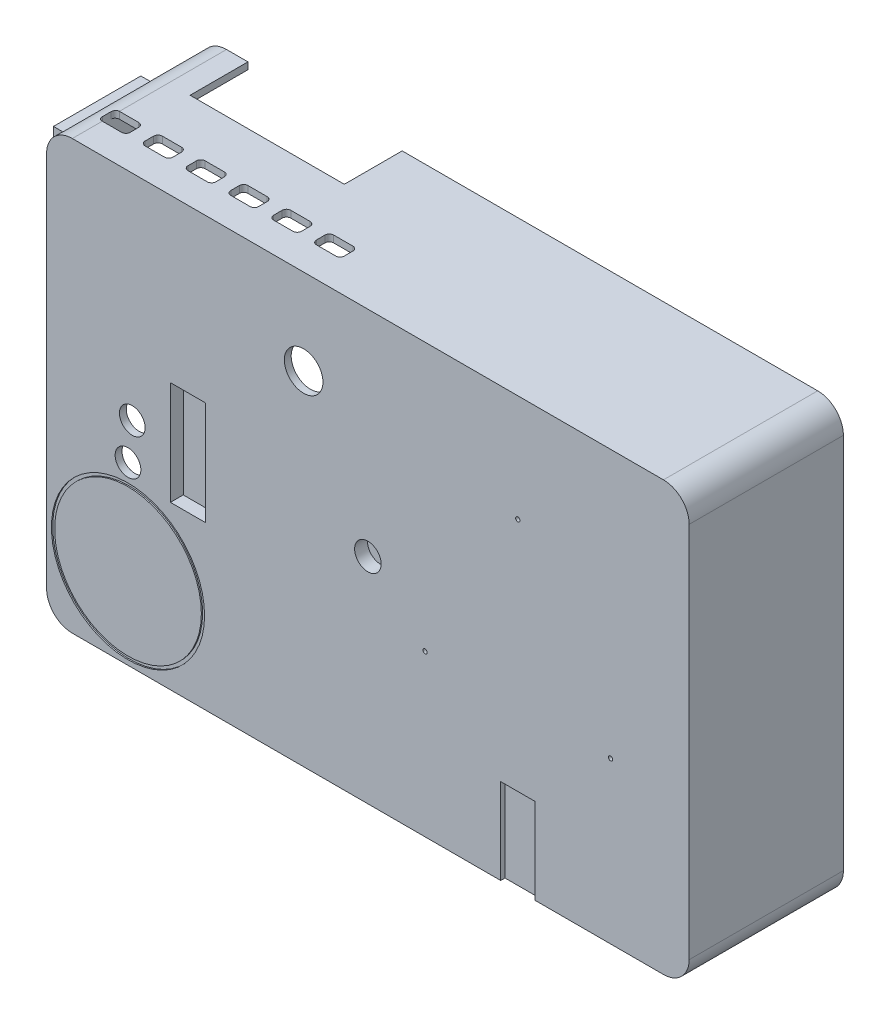
SolidWorks part; units mm, degrees
ref_plane "Front Plane" through (0, 0, 0) normal (0, 0, 1) x (1, 0, 0)
ref_plane "Top Plane" through (0, 0, 0) normal (0, 1, 0) x (1, 0, 0)
ref_plane "Right Plane" through (0, 0, 0) normal (1, 0, 0) x (0, 0, -1)
sketch "Sketch1" plane through (0, 0, 0) normal (0, 0, 1) x (1, 0, 0)
  line L0 (-138, -100) -> (138, -100)
  line L1 (150, -88) -> (150, 88)
  line L2 (138, 100) -> (-138, 100)
  line L3 (-150, 88) -> (-150, -88)
  arc A0 (138, -100) -> (150, -88) centre (138, -88) ccw
  arc A1 (150, 88) -> (138, 100) centre (138, 88) ccw
  arc A2 (-138, 100) -> (-150, 88) centre (-138, 88) ccw
  arc A3 (-150, -88) -> (-138, -100) centre (-138, -88) ccw
extrude "Plinth_block" add sketch "Sketch1" along normal blind 72
ref_plane "Plane_Z+34.15" through (0, 0, 34.15) normal (0, 0, 1) x (1, 0, 0)
sketch "Sketch2" plane through (0, 0, 34.15) normal (0, 0, 1) x (1, 0, 0)
  line L0 (-151, -96.8) -> (-9, -96.8)
  line L1 (-9, -96.8) -> (-9, 96.8)
  line L2 (-9, 96.8) -> (-151, 96.8)
  line L3 (-151, 96.8) -> (-151, -96.8)
  line L4 (3.2, -96.8) -> (137.8, -96.8)
  line L5 (146.8, -87.8) -> (146.8, 87.8)
  line L6 (137.8, 96.8) -> (3.2, 96.8)
  line L7 (-5.8, 87.8) -> (-5.8, -87.8)
  arc A0 (137.8, -96.8) -> (146.8, -87.8) centre (137.8, -87.8) ccw
  arc A1 (146.8, 87.8) -> (137.8, 96.8) centre (137.8, 87.8) ccw
  arc A2 (3.2, 96.8) -> (-5.8, 87.8) centre (3.2, 87.8) ccw
  arc A3 (-5.8, -87.8) -> (3.2, -96.8) centre (3.2, -87.8) ccw
extrude "Hollow_bay_and_front_void" cut sketch "Sketch2" against normal mid plane 69.3
sketch "Sketch3" plane through (0, 0, 0) normal (0, 0, 1) x (1, 0, 0)
  line L0 (-5.8, 38.8) -> (146.8, 38.8)
  line L1 (146.8, 38.8) -> (146.8, 41.2)
  line L2 (146.8, 41.2) -> (-5.8, 41.2)
  line L3 (-5.8, 41.2) -> (-5.8, 38.8)
  line L4 (-5.8, -41.2) -> (146.8, -41.2)
  line L5 (146.8, -41.2) -> (146.8, -38.8)
  line L6 (146.8, -38.8) -> (-5.8, -38.8)
  line L7 (-5.8, -38.8) -> (-5.8, -41.2)
extrude "Dish_support_ribs" add sketch "Sketch3" along normal blind 68.8
ref_plane "Plane_Z+64.00" through (0, 0, 64) normal (0, 0, 1) x (1, 0, 0)
sketch "Sketch4" plane through (0, 0, 64) normal (0, 0, 1) x (1, 0, 0)
  circle A0 centre (70, 0) radius 64
extrude "Dish_floor_thickening" add sketch "Sketch4" along normal blind 4.8
ref_plane "Plane_Z+20.00" through (0, 0, 20) normal (0, 0, 1) x (1, 0, 0)
sketch "Sketch5" plane through (0, 0, 20) normal (0, 0, 1) x (1, 0, 0)
  circle A0 centre (0, 0) radius 12
extrude "Rod_socket_boss" add sketch "Sketch5" along normal blind 48.8
ref_plane "Plane_Z+60.00" through (0, 0, 60) normal (0, 0, 1) x (1, 0, 0)
sketch "Sketch6" plane through (0, 0, 60) normal (0, 0, 1) x (1, 0, 0)
  line L0 (-95, -27) -> (-73, -27)
  line L1 (-73, -27) -> (-73, 27)
  line L2 (-73, 27) -> (-95, 27)
  line L3 (-95, 27) -> (-95, -27)
extrude "Mortise_block" add sketch "Sketch6" along normal blind 8.8
ref_plane "Plane_Z+28.00" through (0, 0, 28) normal (0, 0, 1) x (1, 0, 0)
sketch "Sketch7" plane through (0, 0, 28) normal (0, 0, 1) x (1, 0, 0)
  line L0 (-150, 84) -> (-140, 84)
  line L1 (-140, 84) -> (-140, 97.3)
  line L2 (-140, 97.3) -> (-150, 97.3)
  line L3 (-150, 97.3) -> (-150, 84)
  line L4 (-150, -84) -> (-140, -84)
  line L5 (-140, -84) -> (-140, -97.3)
  line L6 (-140, -97.3) -> (-150, -97.3)
  line L7 (-150, -97.3) -> (-150, -84)
extrude "End_panel_screw_bosses" add sketch "Sketch7" along normal blind 40.8
ref_plane "Plane_Z+69.50" through (0, 0, 69.5) normal (0, 0, 1) x (1, 0, 0)
sketch "Sketch8" plane through (0, 0, 69.5) normal (0, 0, 1) x (1, 0, 0)
  circle A0 centre (0, 0) radius 6.2
  dimension "RodBore" = 12.4
extrude "Rod_socket" cut sketch "Sketch8" against normal mid plane 7
sketch "Sketch9" plane through (0, 0, 69.5) normal (0, 0, 1) x (1, 0, 0)
  line L0 (-92.2, -24.2) -> (-75.8, -24.2)
  line L1 (-75.8, -24.2) -> (-75.8, 24.2)
  line L2 (-75.8, 24.2) -> (-92.2, 24.2)
  line L3 (-92.2, 24.2) -> (-92.2, -24.2)
extrude "Column_mortise" cut sketch "Sketch9" against normal mid plane 7
ref_plane "Plane_Z+70.50" through (0, 0, 70.5) normal (0, 0, 1) x (1, 0, 0)
sketch "Sketch10" plane through (0, 0, 70.5) normal (0, 0, 1) x (1, 0, 0)
  circle A0 centre (70, 50) radius 1
  circle A1 centre (26.6987, -25) radius 1
  circle A2 centre (113.3013, -25) radius 1
extrude "Seat_pin_holes" cut sketch "Sketch10" against normal mid plane 5
ref_plane "Plane_Z+71.50" through (0, 0, 71.5) normal (0, 0, 1) x (1, 0, 0)
sketch "Sketch11" plane through (0, 0, 71.5) normal (0, 0, 1) x (1, 0, 0)
  line L0 (62, -101) -> (78, -101)
  line L1 (78, -101) -> (78, -60)
  line L2 (78, -60) -> (62, -60)
  line L3 (62, -60) -> (62, -101)
extrude "Spill_drain_channel" cut sketch "Sketch11" against normal mid plane 3
ref_plane "Plane_Z+72.20" through (0, 0, 72.2) normal (0, 0, 1) x (1, 0, 0)
sketch "Sketch12" plane through (0, 0, 72.2) normal (0, 0, 1) x (1, 0, 0)
  circle A0 centre (-112, -62) radius 35.75
  circle A1 centre (-112, -62) radius 34.25
extrude "Bottle_position_marker_groove" cut sketch "Sketch12" against normal mid plane 1.6
sketch "Sketch13" plane through (0, 0, 0) normal (0, 0, 1) x (1, 0, 0)
  circle A0 centre (-30, 60) radius 9
  circle A1 centre (-110, 0) radius 6
  circle A2 centre (-112, -18) radius 6
extrude "Cable_grommet_holes" cut sketch "Sketch13" against normal through all and the other way through all
ref_plane "Plane_Y+98.40" through (0, 98.4, 0) normal (0, 1, 0) x (1, 0, 0)
sketch "Sketch14" plane through (0, 98.4, 0) normal (0, 1, 0) x (1, 0, 0)
  line L0 (-128, 1) -> (-56, 1)
  line L1 (-56, 1) -> (-56, -27)
  line L2 (-56, -27) -> (-128, -27)
  line L3 (-128, -27) -> (-128, 1)
  line L4 (-138, -50) -> (-129, -50)
  line L5 (-127, -52) -> (-127, -56)
  line L6 (-129, -58) -> (-138, -58)
  line L7 (-140, -56) -> (-140, -52)
  line L8 (-118, -50) -> (-109, -50)
  line L9 (-107, -52) -> (-107, -56)
  line L10 (-109, -58) -> (-118, -58)
  line L11 (-120, -56) -> (-120, -52)
  line L12 (-98, -50) -> (-89, -50)
  line L13 (-87, -52) -> (-87, -56)
  line L14 (-89, -58) -> (-98, -58)
  line L15 (-100, -56) -> (-100, -52)
  line L16 (-78, -50) -> (-69, -50)
  line L17 (-67, -52) -> (-67, -56)
  line L18 (-69, -58) -> (-78, -58)
  line L19 (-80, -56) -> (-80, -52)
  line L20 (-58, -50) -> (-49, -50)
  line L21 (-47, -52) -> (-47, -56)
  line L22 (-49, -58) -> (-58, -58)
  line L23 (-60, -56) -> (-60, -52)
  line L24 (-38, -50) -> (-29, -50)
  line L25 (-27, -52) -> (-27, -56)
  line L26 (-29, -58) -> (-38, -58)
  line L27 (-40, -56) -> (-40, -52)
  arc A0 (-129, -50) -> (-127, -52) centre (-129, -52) cw
  arc A1 (-127, -56) -> (-129, -58) centre (-129, -56) cw
  arc A2 (-138, -58) -> (-140, -56) centre (-138, -56) cw
  arc A3 (-140, -52) -> (-138, -50) centre (-138, -52) cw
  arc A4 (-109, -50) -> (-107, -52) centre (-109, -52) cw
  arc A5 (-107, -56) -> (-109, -58) centre (-109, -56) cw
  arc A6 (-118, -58) -> (-120, -56) centre (-118, -56) cw
  arc A7 (-120, -52) -> (-118, -50) centre (-118, -52) cw
  arc A8 (-89, -50) -> (-87, -52) centre (-89, -52) cw
  arc A9 (-87, -56) -> (-89, -58) centre (-89, -56) cw
  arc A10 (-98, -58) -> (-100, -56) centre (-98, -56) cw
  arc A11 (-100, -52) -> (-98, -50) centre (-98, -52) cw
  arc A12 (-69, -50) -> (-67, -52) centre (-69, -52) cw
  arc A13 (-67, -56) -> (-69, -58) centre (-69, -56) cw
  arc A14 (-78, -58) -> (-80, -56) centre (-78, -56) cw
  arc A15 (-80, -52) -> (-78, -50) centre (-78, -52) cw
  arc A16 (-49, -50) -> (-47, -52) centre (-49, -52) cw
  arc A17 (-47, -56) -> (-49, -58) centre (-49, -56) cw
  arc A18 (-58, -58) -> (-60, -56) centre (-58, -56) cw
  arc A19 (-60, -52) -> (-58, -50) centre (-58, -52) cw
  arc A20 (-29, -50) -> (-27, -52) centre (-29, -52) cw
  arc A21 (-27, -56) -> (-29, -58) centre (-29, -56) cw
  arc A22 (-38, -58) -> (-40, -56) centre (-38, -56) cw
  arc A23 (-40, -52) -> (-38, -50) centre (-38, -52) cw
extrude "Pi_side_port_notch_and_vents" cut sketch "Sketch14" against normal mid plane 5.2
ref_plane "Plane_X-144.50" through (-144.5, 0, 0) normal (1, 0, 0) x (0, 0, -1)
sketch "Sketch15" plane through (-144.5, 0, 0) normal (1, 0, 0) x (0, 0, -1)
  circle A0 centre (-35, 90) radius 1.3
  circle A1 centre (-35, -90) radius 1.3
extrude "End_panel_screw_holes" cut sketch "Sketch15" against normal mid plane 13
